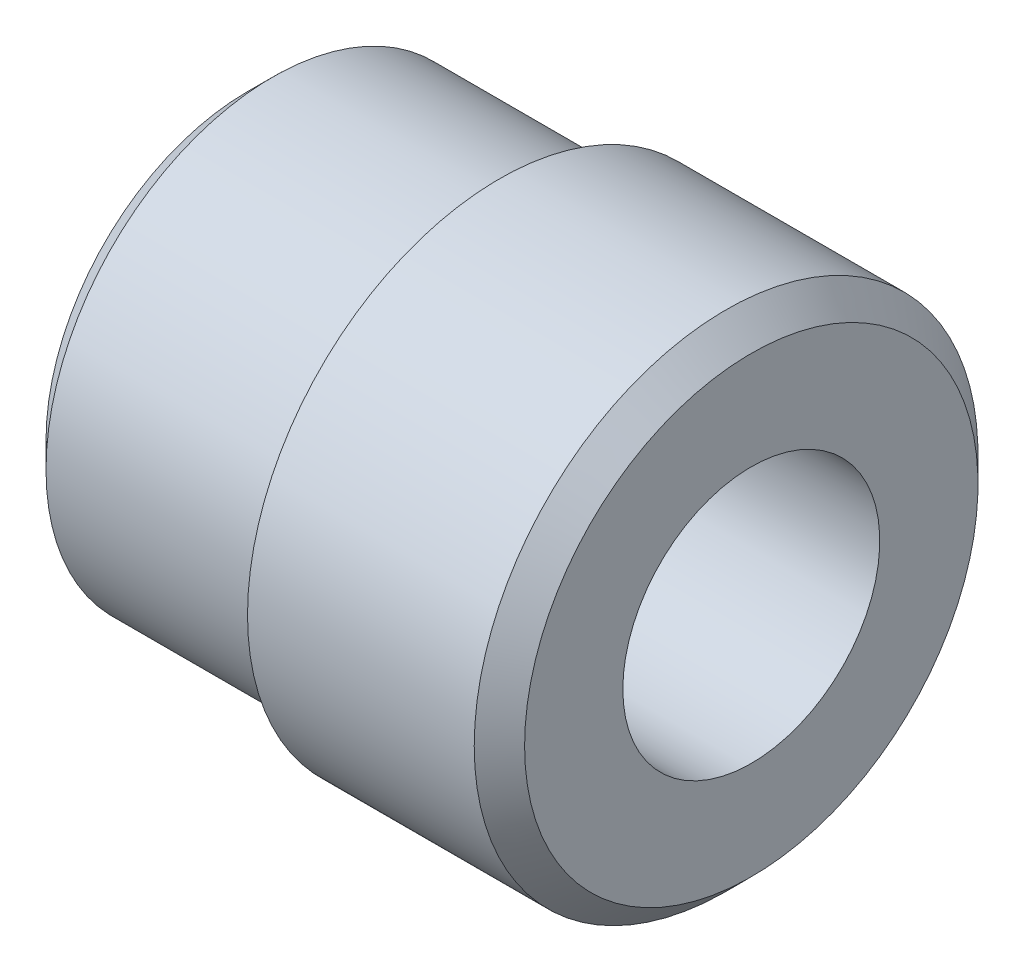
SolidWorks part; units mm, degrees
material "AISI 304"
ref_plane "Спереди" through (0, 0, 0) normal (0, 0, 1) x (1, 0, 0)
ref_plane "Сверху" through (0, 0, 0) normal (0, 1, 0) x (1, 0, 0)
ref_plane "Справа" through (0, 0, 0) normal (1, 0, 0) x (0, 0, -1)
sketch "Эскиз1" plane through (0, 0, 0) normal (0, 0, 1) x (1, 0, 0)
  line L0 (0, 0) -> (20, 0) construction
  line L1 (0, 5) -> (0, 9)
  line L2 (0, 9) -> (10, 9)
  line L3 (10, 9) -> (10, 10)
  line L4 (10, 10) -> (20, 10)
  line L5 (20, 10) -> (20, 5)
  line L6 (20, 5) -> (0, 5)
  dimension "D1" = 10
  dimension "D2" = 10
  dimension "D3" = 10
  dimension "D4" = 18
  dimension "D5" = 20
revolve "Повернуть1" add sketch "Эскиз1" angle 360 about L0
hole_wizard "Отверстие обработанное метчиком M121" positions "Эскиз2" profile "Эскиз3" tap size "M12" standard "DIN" end condition through all
sketch "Эскиз2" plane through (0, 0, 0) normal (-1, 0, 0) x (0, 0, 1)
  point P0 (0, 0)
sketch "Эскиз3" plane through (0, 0, 0) normal (0, 1, 0) x (0, 0, 1)
  line L0 (0, 0) -> (0, 20)
  line L1 (0, 20) -> (5.1, 20)
  line L2 (5.1, 20) -> (5.1, 0)
  line L5 (5.1, 0) -> (0, 0)
  line L11 (0, -6.35) -> (0, 107.95) construction
  dimension "Диаметр проходного сверла" = 10.2
  dimension "Глубина проходного сверла" = 20
cosmetic thread "Отверстие резьбы1" parameters "D2"=12
chamfer "Фаска1" distance 1 angle 45 2 edges at (0, 0, 9) (20, 0, 10)
